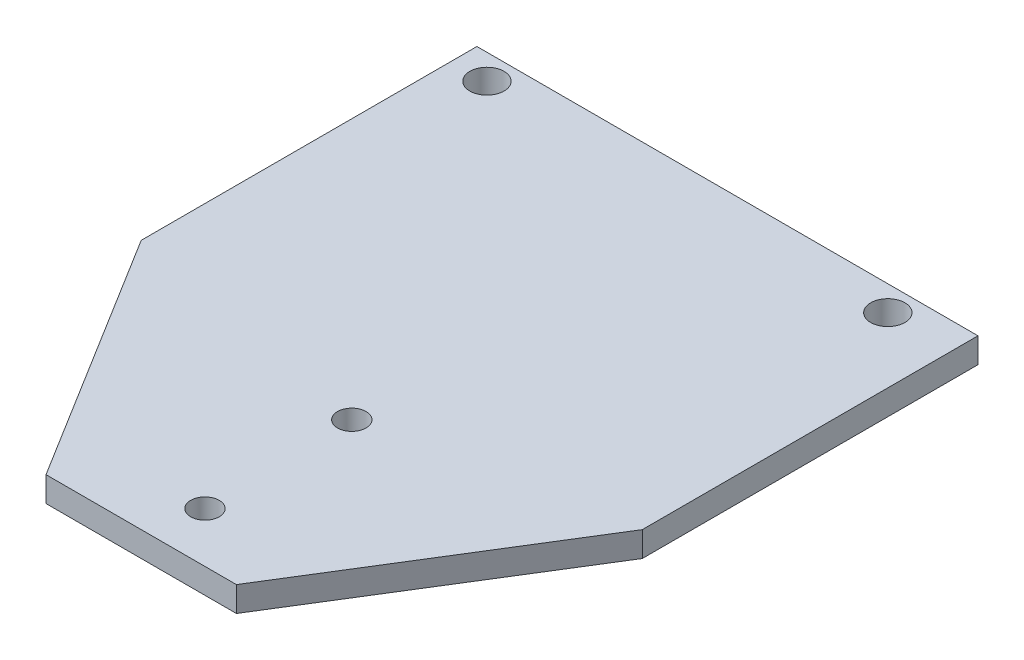
SolidWorks part; units mm, degrees
ref_plane "Front Plane" through (0, 0, 0) normal (0, 0, 1) x (1, 0, 0)
ref_plane "Top Plane" through (0, 0, 0) normal (0, 1, 0) x (1, 0, 0)
ref_plane "Right Plane" through (0, 0, 0) normal (1, 0, 0) x (0, 0, -1)
sketch "Sketch1" plane through (0, 0, 0) normal (0, 1, 0) x (1, 0, 0)
  line L0 (50, 67) -> (50, 0) construction
  line L2 (0, 0) -> (0, 67)
  line L4 (100, 0) -> (100, 67)
  line L5 (31, -50) -> (69, -50)
  line L6 (31, -50) -> (0, 0)
  line L7 (69, -50) -> (100, 0)
  line L8 (50, 0) -> (50, -50) construction
  line L12 (0, 67) -> (100, 67)
  circle A1 centre (87, 62) radius 3.4151
  circle A5 centre (7, 62) radius 3.415
  dimension "D4" = 6.8302
  dimension "D2" = 6.83
  dimension "D1" = 100
  dimension "D6" = 7
  dimension "D7" = 19
  dimension "D8" = 50
  dimension "D9" = 87
  dimension "D10" = 50
extrude "Boss-Extrude1" add sketch "Sketch1" along normal blind 5
sketch "Sketch2" plane through (0, 5, 0) normal (0, 1, 0) x (1, 0, 0)
  line L0 (52.9511, -50) -> (50, 78)
  line L1 (31, -50) -> (69, -50) construction
  line L2 (100, 78) -> (0, 78) construction
  circle A0 centre (52.7205, -40) radius 2.85
  circle A1 centre (52.0289, -10) radius 2.85
  dimension "D1" = 5.7
  dimension "D2" = 5.7
  dimension "D3" = 30
  dimension "D4" = 10
extrude "Cut-Extrude1" cut sketch "Sketch2" against normal through all both and the other way through all contours A1 | A0
